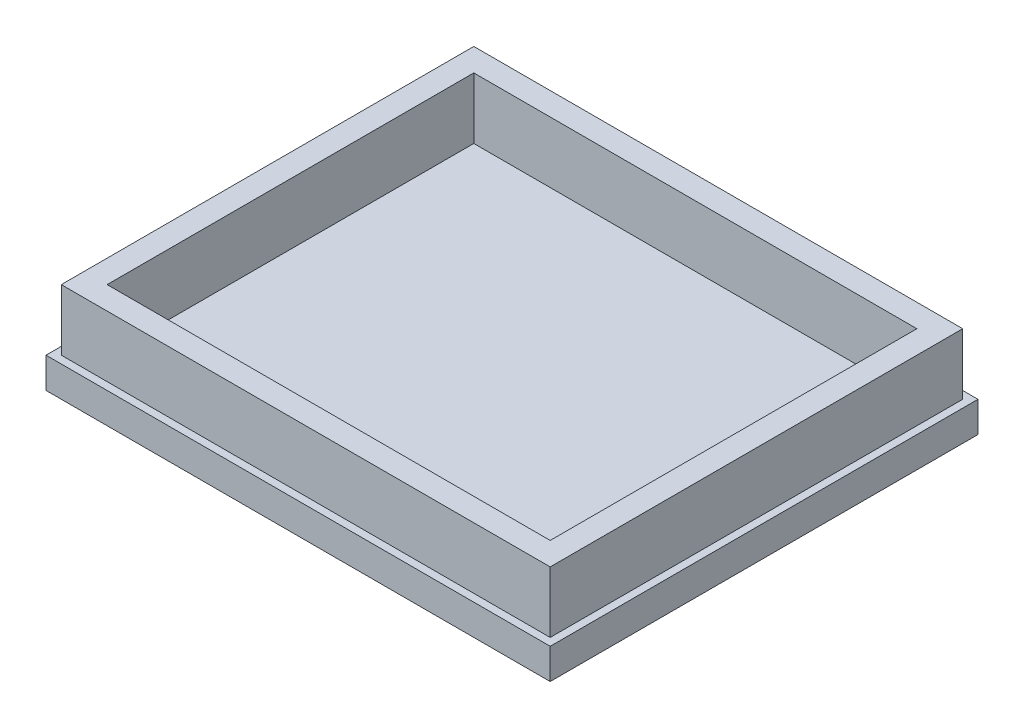
SolidWorks part; units mm, degrees
ref_plane "前视基准面" through (0, 0, 0) normal (0, 0, 1) x (1, 0, 0)
ref_plane "上视基准面" through (0, 0, 0) normal (0, 1, 0) x (1, 0, 0)
ref_plane "右视基准面" through (0, 0, 0) normal (1, 0, 0) x (0, 0, -1)
sketch "草图1" plane through (0, 0, 0) normal (0, 1, 0) x (1, 0, 0)
  line L1 (0, 0) -> (33, 0)
  line L2 (0, 0) -> (0, -28)
  line L3 (0, -28) -> (33, -28)
  line L4 (33, 0) -> (33, -28)
  dimension "D1" = 33
  dimension "D2" = 28
extrude "凸台-拉伸1" add sketch "草图1" along normal blind 2
sketch "草图2" plane through (0, 2, 0) normal (0, 1, 0) x (1, 0, 0)
  line L0 (0, -28) -> (33, -28) construction
  line L1 (2, -26) -> (31, -26)
  line L2 (2, -26) -> (2, -2)
  line L3 (2, -2) -> (31, -2)
  line L4 (31, -26) -> (31, -2)
  line L5 (0, 0) -> (0, -28) construction
  line L6 (0.5, -27.5) -> (0.5, -0.5)
  line L7 (0.5, -0.5) -> (32.5, -0.5)
  line L8 (32.5, -27.5) -> (32.5, -0.5)
  line L9 (0.5, -27.5) -> (32.5, -27.5)
  dimension "D1" = 29
  dimension "D2" = 24
  dimension "D3" = 2
  dimension "D4" = 2
  dimension "D5" = 1.5
extrude "凸台-拉伸2" add sketch "草图2" along normal blind 4
